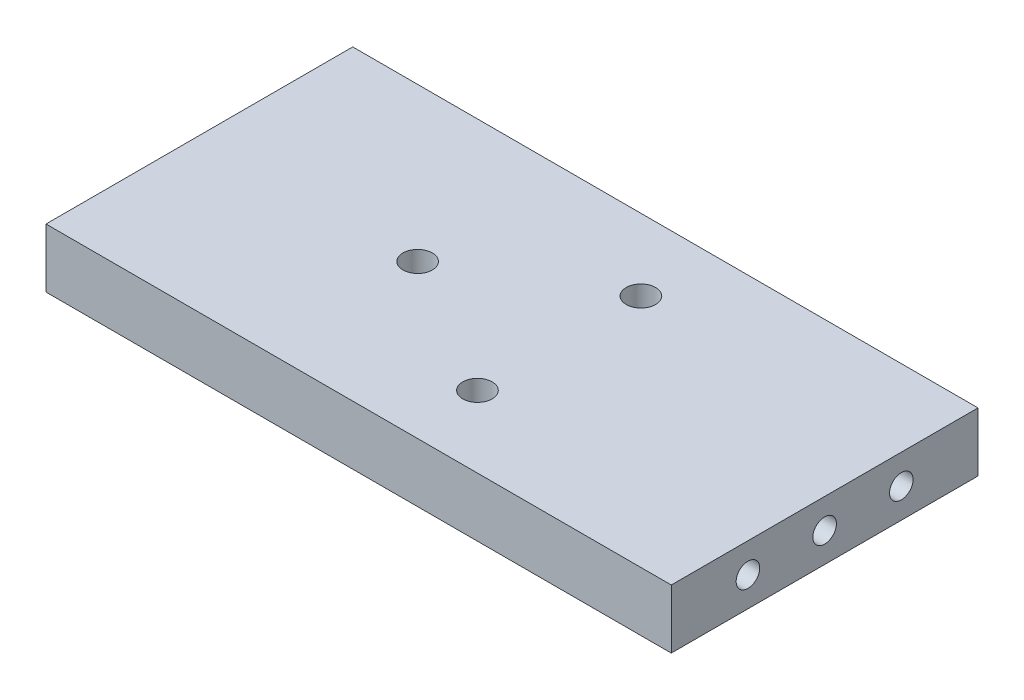
SolidWorks part; units mm, degrees
ref_plane "Front Plane" through (0, 0, 0) normal (0, 0, 1) x (1, 0, 0)
ref_plane "Top Plane" through (0, 0, 0) normal (0, 1, 0) x (1, 0, 0)
ref_plane "Right Plane" through (0, 0, 0) normal (1, 0, 0) x (0, 0, -1)
sketch "Sketch1" plane through (0, 0, 0) normal (0, 1, 0) x (1, 0, 0)
  line L1 (0, 0) -> (53, 0)
  line L2 (0, 0) -> (0, 26)
  line L3 (0, 26) -> (53, 26)
  line L4 (53, 0) -> (53, 26)
  dimension "53" = 53
  dimension "D2" = 26
extrude "Boss-Extrude1" add sketch "Sketch1" along normal blind 5
sketch "Sketch4" plane through (53, 0, 0) normal (1, 0, 0) x (0, 0, -1)
  line L1 (0, 5) -> (0, 0) construction
  line L10 (0, 0) -> (0, 2.5)
  line L11 (0, 2.5) -> (0, 5)
  line L15 (0, 5) -> (26, 5) construction
  circle A0 centre (6.5, 2.5) radius 1
  circle A1 centre (13, 2.5) radius 1
  circle A2 centre (19.5, 2.5) radius 1
  dimension "D1" = 2
  dimension "D2" = 2.5
  dimension "D3" = 6.5
hole_wizard "Ø2.0mm Dowel Hole4" positions "3DSketch4" profile "Sketch8" hole size "Ø2.0" standard "ANSI Metric"
sketch3d "3DSketch4"
  point P0 (53, 2.5, -6.5)
  point P3 (53, 2.5, -13)
  point P6 (53, 2.5, -19.5)
sketch "Sketch8" plane through (53, 2.5, -6.5) normal (0, 1, 0) x (0, 0, -1)
  line L0 (0, 0) -> (0, 7.6009)
  line L1 (0, 7.6009) -> (1, 7)
  line L2 (1, 7) -> (1, 0)
  line L5 (1, 0) -> (0, 0)
  line L10 (0, 7.6009) -> (-1, 7) construction
  line L11 (0, -6.35) -> (0, 107.95) construction
  dimension "Hole Dia." = 2
  dimension "Hole Depth" = 7
  dimension "Drill Angle" = 118
sketch "Sketch11" plane through (0, 0, 0) normal (-1, 0, 0) x (0, 0, 1)
  line L0 (-26, 5) -> (-26, 0) construction
  line L1 (-26, 5) -> (0, 5) construction
  circle A0 centre (-19.5, 2.5) radius 1
  circle A1 centre (-13, 2.5) radius 1
  circle A2 centre (-6.5, 2.5) radius 1
  point P0 (-19.5, 2.5)
  point P2 (-13, 2.5)
  point P4 (-6.5, 2.5)
  dimension "D2" = 2
  dimension "D1" = 6.5
  dimension "D3" = 2.5
  dimension "D4" = 2.5
  dimension "D5" = 2.5
  dimension "D6" = 6.5
  dimension "D7" = 6.5
hole_wizard "Ø2.0mm Dowel Hole6" positions "Sketch11" profile "Sketch12" hole size "Ø2.0" standard "ANSI Metric"
sketch "Sketch12" plane through (0, 2.5, -19.5) normal (0, 1, 0) x (0, 0, 1)
  line L0 (0, 0) -> (0, 7.6009)
  line L1 (0, 7.6009) -> (1, 7)
  line L2 (1, 7) -> (1, 0)
  line L5 (1, 0) -> (0, 0)
  line L10 (0, 7.6009) -> (-1, 7) construction
  line L11 (0, -6.35) -> (0, 107.95) construction
  dimension "Hole Dia." = 2
  dimension "Hole Depth" = 7
  dimension "Drill Angle" = 118
sketch "Sketch13" plane through (0, 5, 0) normal (0, 1, 0) x (1, 0, 0)
  line L1 (0, 26) -> (0, 0) construction
  circle A0 centre (26.5, 13) radius 8
  circle A1 centre (18.5, 13) radius 1.25
  circle A2 centre (30.5, 19.9282) radius 1.25
  circle A3 centre (30.5, 6.0718) radius 1.25
  dimension "D1" = 16
  dimension "D2" = 2.5
  dimension "D3" = 26.5
hole_wizard "Ø2.5mm Dowel Hole1" positions "3DSketch5" profile "Sketch15" hole size "Ø2.5" standard "ANSI Metric"
sketch3d "3DSketch5"
  point P0 (18.5, 5, -13)
  point P3 (30.5, 5, -19.9282)
  point P6 (30.5, 5, -6.0718)
sketch "Sketch15" plane through (18.5, 5, -13) normal (1, 0, 0) x (0, 0, 1)
  line L0 (0, 0) -> (0, 5.7511)
  line L1 (0, 5.7511) -> (1.25, 5)
  line L2 (1.25, 5) -> (1.25, 0)
  line L5 (1.25, 0) -> (0, 0)
  line L10 (0, 5.7511) -> (-1.25, 5) construction
  line L11 (0, -6.35) -> (0, 107.95) construction
  dimension "Hole Dia." = 2.5
  dimension "Hole Depth" = 5
  dimension "Drill Angle" = 118
